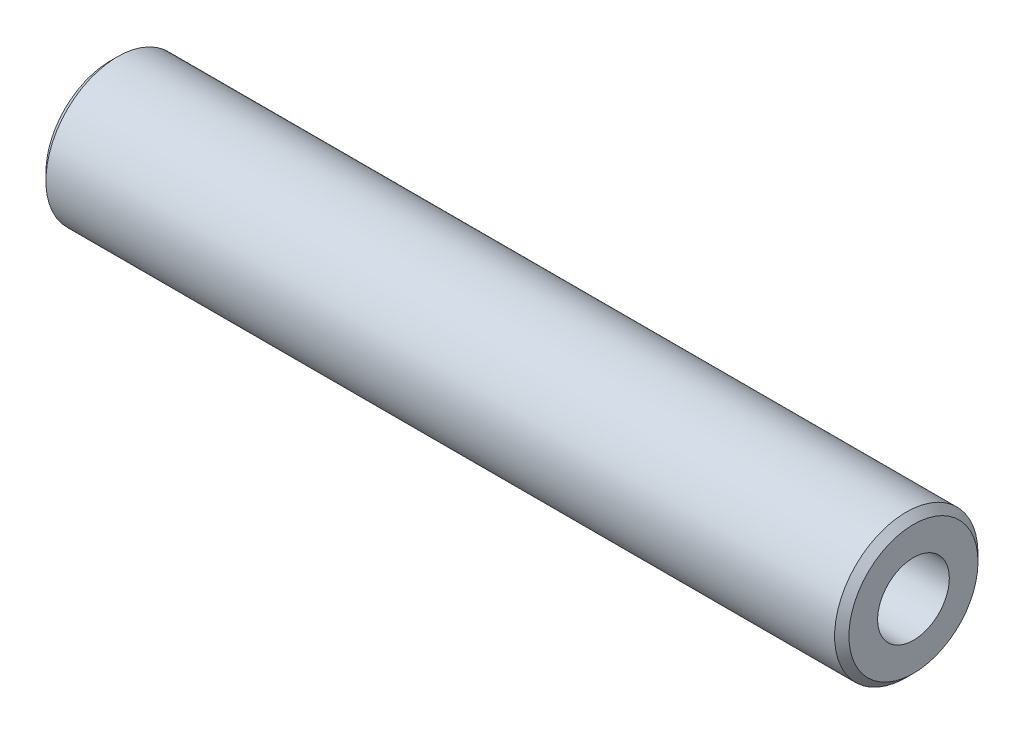
SolidWorks part; units mm, degrees
ref_plane "Front Plane" through (0, 0, 0) normal (0, 0, 1) x (1, 0, 0)
ref_plane "Top Plane" through (0, 0, 0) normal (0, 1, 0) x (1, 0, 0)
ref_plane "Right Plane" through (0, 0, 0) normal (1, 0, 0) x (0, 0, -1)
sketch "Sketch1" plane through (0, 0, 0) normal (1, 0, 0) x (0, 0, -1)
  circle A0 centre (0, 0) radius 2.5
  circle A1 centre (0, 0) radius 5
  dimension "D1" = 5
  dimension "D2" = 2.5
extrude "Boss-Extrude1" add sketch "Sketch1" along normal mid plane 56
chamfer "Chamfer1" distance 0.5 angle 45 2 edges at (-28, 0, -5) (28, 0, -5)
